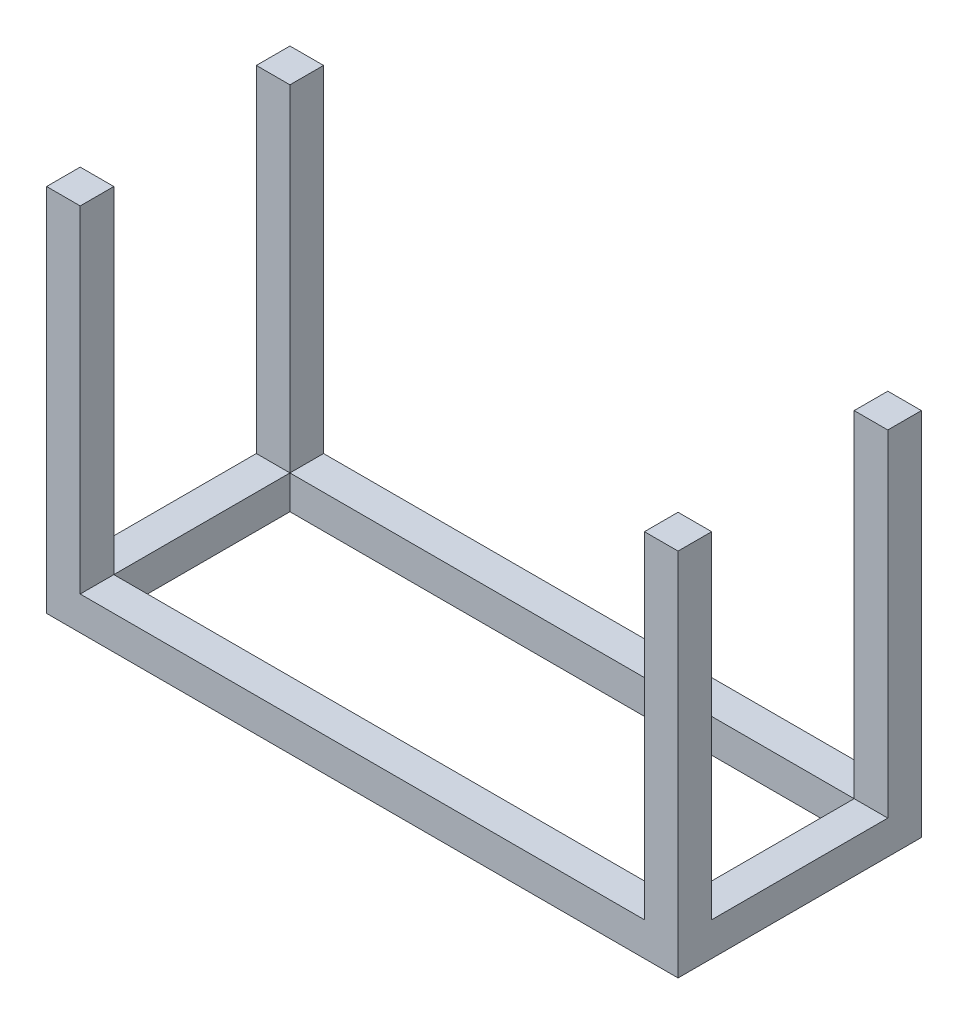
SolidWorks part; units mm, degrees
ref_plane "Front Plane" through (0, 0, 0) normal (0, 0, 1) x (1, 0, 0)
ref_plane "Top Plane" through (0, 0, 0) normal (0, 1, 0) x (1, 0, 0)
ref_plane "Right Plane" through (0, 0, 0) normal (1, 0, 0) x (0, 0, -1)
sketch "Sketch1" plane through (0, 0, 0) normal (0, 1, 0) x (1, 0, 0)
  line L1 (-62.95, -19.65) -> (62.95, -19.65)
  line L2 (-62.95, -19.65) -> (-62.95, 19.65)
  line L3 (-62.95, 19.65) -> (62.95, 19.65)
  line L4 (62.95, -19.65) -> (62.95, 19.65)
  line L5 (-62.95, -19.65) -> (62.95, 19.65) construction
  line L6 (-62.95, 19.65) -> (62.95, -19.65) construction
  line L7 (-70.45, -27.15) -> (70.45, -27.15)
  line L8 (-70.45, -27.15) -> (-70.45, 27.15)
  line L9 (-70.45, 27.15) -> (70.45, 27.15)
  line L10 (70.45, -27.15) -> (70.45, 27.15)
  line L11 (-70.45, -27.15) -> (70.45, 27.15) construction
  line L12 (-70.45, 27.15) -> (70.45, -27.15) construction
  point P0 (0, 0)
  point P6 (0, 0)
  dimension "D1" = 125.9
  dimension "D2" = 39.3
  dimension "D3" = 140.9
  dimension "D4" = 54.3
extrude "Boss-Extrude1" add sketch "Sketch1" along normal blind 7.5
sketch "Sketch2" plane through (0, 7.5, 0) normal (0, 1, 0) x (1, 0, 0)
  line L0 (70.45, 27.15) -> (-70.45, 27.15) construction
  line L1 (-70.45, 27.15) -> (-62.95, 27.15)
  line L2 (-70.45, 27.15) -> (-70.45, 19.65)
  line L3 (-70.45, 19.65) -> (-62.95, 19.65)
  line L4 (-62.95, 27.15) -> (-62.95, 19.65)
  line L5 (62.95, 19.65) -> (70.45, 19.65)
  line L6 (62.95, 19.65) -> (62.95, 27.15)
  line L7 (62.95, 27.15) -> (70.45, 27.15)
  line L8 (70.45, 19.65) -> (70.45, 27.15)
  line L9 (70.45, -27.15) -> (70.45, 27.15) construction
  line L10 (-62.95, -19.65) -> (62.95, -19.65) construction
  line L11 (62.95, -19.65) -> (70.45, -19.65)
  line L12 (62.95, -19.65) -> (62.95, -27.15)
  line L13 (62.95, -27.15) -> (70.45, -27.15)
  line L14 (70.45, -19.65) -> (70.45, -27.15)
  line L15 (62.95, -19.65) -> (62.95, 19.65) construction
  line L16 (-70.45, -27.15) -> (70.45, -27.15) construction
  line L17 (-62.95, -19.65) -> (-70.45, -19.65)
  line L18 (-62.95, -19.65) -> (-62.95, -27.15)
  line L19 (-62.95, -27.15) -> (-70.45, -27.15)
  line L20 (-70.45, -19.65) -> (-70.45, -27.15)
  line L21 (-70.45, 27.15) -> (-70.45, -27.15) construction
  line L22 (-62.95, 23.4) -> (62.95, 23.4) construction
  line L23 (62.95, 23.4) -> (66.7, 19.65) construction
  line L24 (66.7, 19.65) -> (66.7, -19.65) construction
  line L25 (66.7, -19.65) -> (62.95, -23.4) construction
  line L26 (62.95, -23.4) -> (-62.95, -23.4) construction
  line L27 (-62.95, -23.4) -> (-66.7, -19.65) construction
  line L28 (-66.7, -19.65) -> (-66.7, 19.65) construction
  line L29 (-66.7, 19.65) -> (-62.95, 23.4) construction
  dimension "D1" = 7.5
  dimension "D2" = 7.5
  dimension "D3" = 125.9
  dimension "D4" = 39.3
extrude "Boss-Extrude2" add sketch "Sketch2" along normal blind 75
